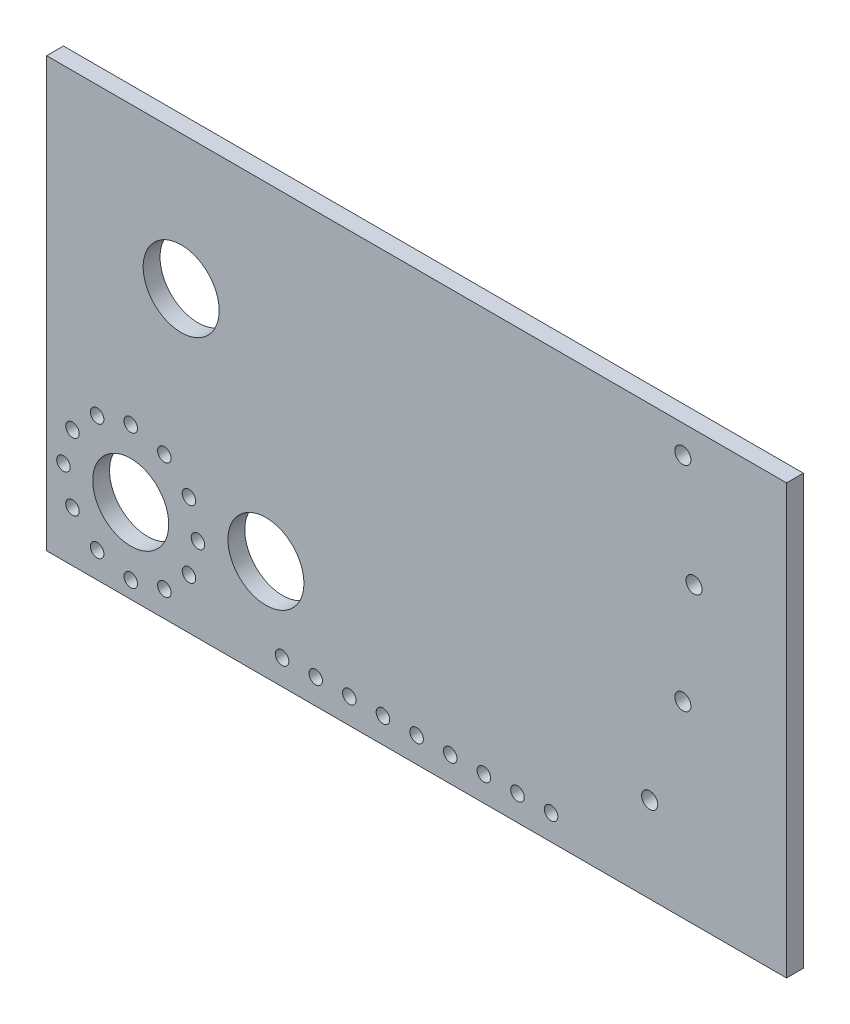
SolidWorks part; units mm, degrees
material "6061-T6 (SS)"
ref_plane "Front Plane" through (0, 0, 0) normal (0, 0, 1) x (1, 0, 0)
ref_plane "Top Plane" through (0, 0, 0) normal (0, 1, 0) x (1, 0, 0)
ref_plane "Right Plane" through (0, 0, 0) normal (1, 0, 0) x (0, 0, -1)
sketch "Sketch1" plane through (0, 0, 0) normal (0, 0, 1) x (1, 0, 0)
  line L0 (0, 0) -> (12.7, 0) construction
  line L1 (0, 0) -> (0, -9.525) construction
  line L2 (0, -9.525) -> (-139.7, -9.525)
  line L3 (0, -9.525) -> (139.7, -9.525)
  line L4 (-139.7, -9.525) -> (-139.7, 152.4)
  line L5 (-139.7, 152.4) -> (139.7, 152.4)
  line L6 (139.7, 152.4) -> (139.7, -9.525)
  line L7 (88.0309, 22.8253) -> (100.5427, 61.3327) construction
  line L8 (100.5427, 61.3327) -> (104.775, 101.6) construction
  line L9 (104.775, 101.6) -> (100.5427, 141.8673) construction
  line L10 (88.0309, 22.8253) -> (-88.9, 101.6) construction
  line L11 (-88.9, 101.6) -> (100.5427, 61.3327) construction
  line L12 (104.775, 101.6) -> (-88.9, 101.6) construction
  line L13 (-88.9, 101.6) -> (100.5427, 141.8673) construction
  line L14 (-50.8, 0) -> (-56.8937, 28.4238) construction
  line L15 (-56.8937, 28.4238) -> (-68.5428, 55.0573) construction
  line L16 (-68.5428, 55.0573) -> (-88.9, 101.6) construction
  line L17 (-107.95, 22.225) -> (-78.1687, 25.8408) construction
  line L18 (-78.1687, 25.8408) -> (-75.8048, 26.1278) construction
  line L19 (-75.8048, 26.1278) -> (-56.8937, 28.4238) construction
  circle A0 centre (0, 0) radius 2.5527
  circle A1 centre (12.7, 0) radius 2.5527
  circle A2 centre (25.4, 0) radius 2.5527
  circle A3 centre (38.1, 0) radius 2.5527
  circle A4 centre (50.8, 0) radius 2.5527
  circle A5 centre (-50.8, 0) radius 2.5527
  circle A6 centre (-38.1, 0) radius 2.5527
  circle A7 centre (-25.4, 0) radius 2.5527
  circle A8 centre (-12.7, 0) radius 2.5527
  circle A9 centre (-88.9, 101.6) radius 50.8 construction
  circle A10 centre (-107.95, 22.225) radius 30 construction
  circle A11 centre (-107.95, 22.225) radius 25.4 construction
  circle A12 centre (-82.55, 22.225) radius 2.5527
  circle A13 centre (-85.953, 9.525) radius 2.5527
  circle A14 centre (-95.25, 0.228) radius 2.5527
  circle A15 centre (-107.95, -3.175) radius 2.5527
  circle A16 centre (-120.65, 0.228) radius 2.5527
  circle A17 centre (-129.947, 9.525) radius 2.5527
  circle A18 centre (-133.35, 22.225) radius 2.5527
  circle A19 centre (-129.947, 34.925) radius 2.5527
  circle A20 centre (-120.65, 44.222) radius 2.5527
  circle A21 centre (-107.95, 47.625) radius 2.5527
  circle A22 centre (-95.25, 44.222) radius 2.5527
  circle A23 centre (-85.953, 34.925) radius 2.5527
  arc A24 (88.0309, 22.8253) -> (100.5427, 141.8673) centre (-88.9, 101.6) ccw construction
  circle A25 centre (100.5427, 141.8673) radius 3.048
  circle A26 centre (104.775, 101.6) radius 3.048
  circle A27 centre (100.5427, 61.3327) radius 3.048
  circle A28 centre (88.0309, 22.8253) radius 3.048
  circle A30 centre (-107.95, 22.225) radius 14.351
  circle A31 centre (-88.9, 101.6) radius 14.351
  circle A32 centre (-56.8937, 28.4238) radius 14.351
  circle A33 centre (-56.8937, 28.4238) radius 19.05 construction
  point P55 (-107.95, 22.225)
  dimension "D1" = 5.1054
  dimension "D6" = 101.6
  dimension "D7" = 60
  dimension "D8" = 50.8
  dimension "D12" = 193.675
  dimension "D13" = 6.096
  dimension "D16" = 28.702
  dimension "D17" = 38.1
  dimension "D18" = 2.3813
  dimension "D3" = 12.7
  dimension "D4" = 9.525
  dimension "D5" = 139.7
  dimension "D10" = 31.75
  dimension "D11" = 31.75
  dimension "D14" = 12
  dimension "D15" = 111.125
  dimension "D2" = 5
  dimension "D9" = 12
extrude "Boss-Extrude1" add sketch "Sketch1" along normal blind 6.35
